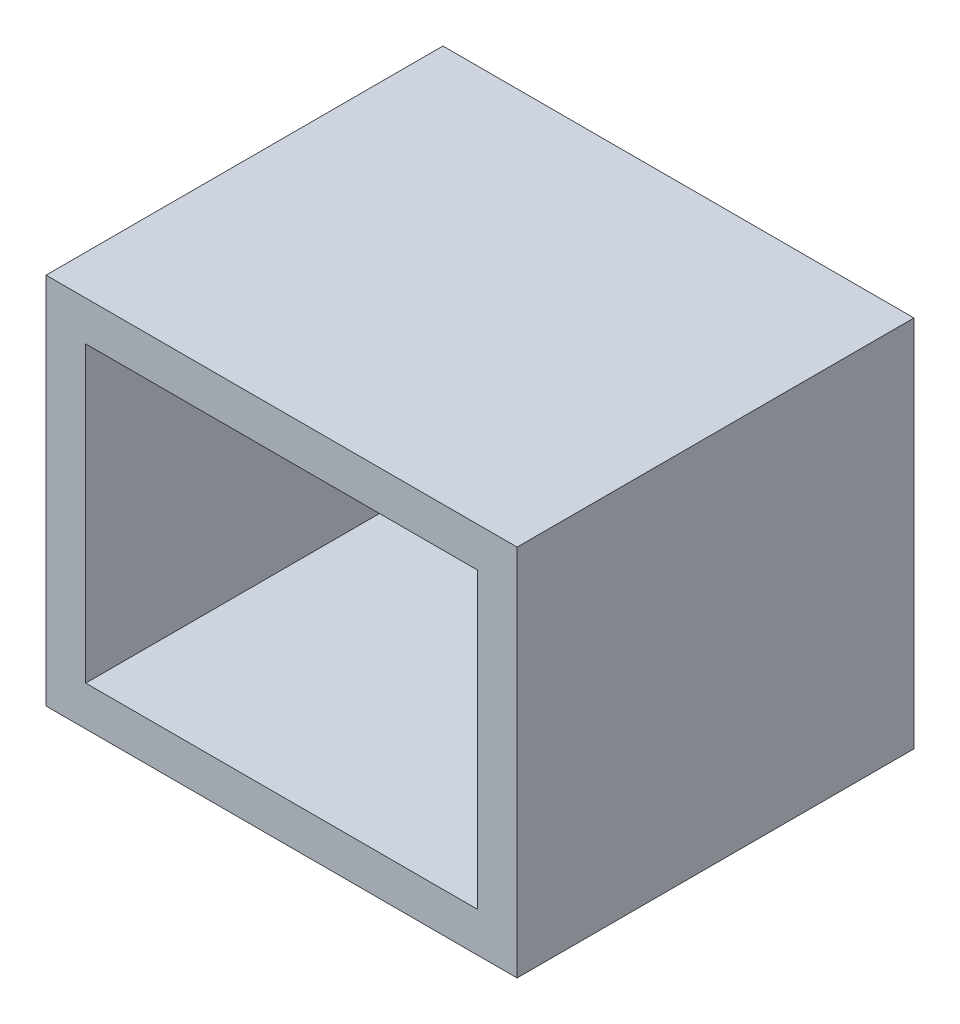
SolidWorks part; units mm, degrees
ref_plane "Front Plane" through (0, 0, 0) normal (0, 0, 1) x (1, 0, 0)
ref_plane "Top Plane" through (0, 0, 0) normal (0, 1, 0) x (1, 0, 0)
ref_plane "Right Plane" through (0, 0, 0) normal (1, 0, 0) x (0, 0, -1)
sketch "Sketch2" plane through (0, 0, 0) normal (0, 0, 1) x (1, 0, 0)
  line L0 (2.54, 2.54) -> (27.6058, 2.54)
  line L1 (0, 0) -> (30.1458, 0)
  line L2 (0, 0) -> (0, 23.8822)
  line L3 (0, 23.8822) -> (30.1458, 23.8822)
  line L4 (30.1458, 0) -> (30.1458, 23.8822)
  line L5 (27.6058, 2.54) -> (27.6058, 21.3422)
  line L6 (2.54, 21.3422) -> (27.6058, 21.3422)
  line L7 (2.54, 2.54) -> (2.54, 21.3422)
  dimension "D1" = 2.54
extrude "Boss-Extrude1" add sketch "Sketch2" along normal blind 25.4
